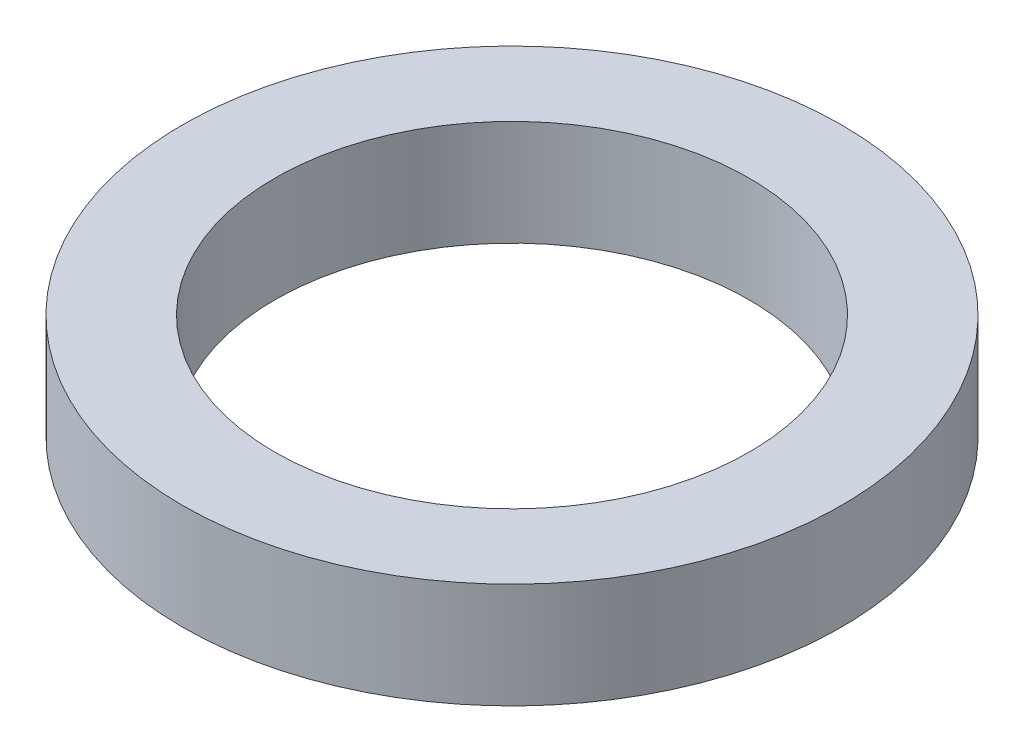
SolidWorks part; units mm, degrees
ref_plane "前视基准面" through (0, 0, 0) normal (0, 0, 1) x (1, 0, 0)
ref_plane "上视基准面" through (0, 0, 0) normal (0, 1, 0) x (1, 0, 0)
ref_plane "右视基准面" through (0, 0, 0) normal (1, 0, 0) x (0, 0, -1)
sketch "草图1" plane through (0, 0, 0) normal (0, 1, 0) x (1, 0, 0)
  circle A0 centre (0, 0) radius 45
  circle A1 centre (0, 0) radius 62.5
  dimension "D1" = 90
  dimension "D2" = 125
extrude "凸台-拉伸1" add sketch "草图1" along normal blind 20
